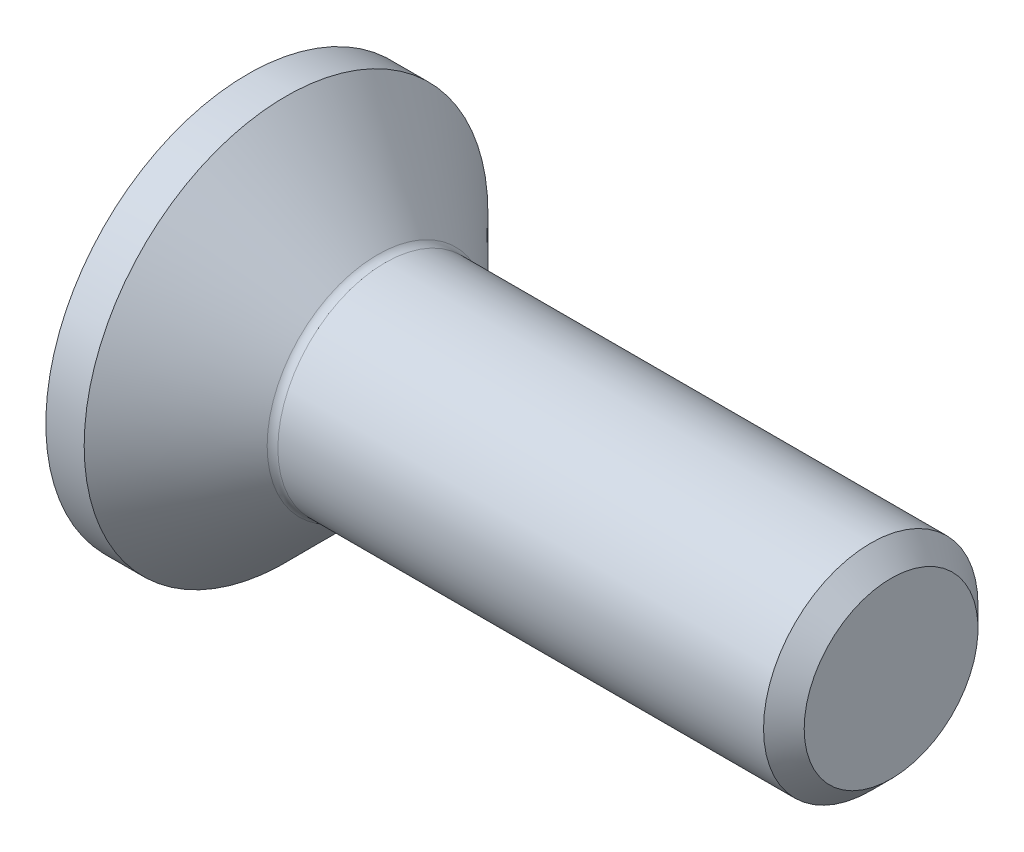
SolidWorks part; units mm, degrees
ref_plane "Front" through (0, 0, 0) normal (0, 0, 1) x (1, 0, 0)
ref_plane "Top" through (0, 0, 0) normal (0, 1, 0) x (1, 0, 0)
ref_plane "Right" through (0, 0, 0) normal (1, 0, 0) x (0, 0, -1)
sketch "Sketch1" plane through (0, 0, 0) normal (0, 0, 1) x (1, 0, 0)
  line L0 (0, 0) -> (0, 4.48)
  line L1 (0, 4.48) -> (2.48, 2)
  line L2 (2.48, 2) -> (12, 2)
  line L3 (12, 2) -> (12, 0)
  line L4 (12, 0) -> (0, 0)
  line L5 (-0.5871, 0) -> (5.4927, 0) construction
  dimension "l" = 12
  dimension "k" = 2.48
  dimension "d" = 4
  dimension "D1" = 45
revolve "Base" add sketch "Sketch1" angle 360 about L5
cosmetic thread "ThreadCosmetic1" parameters "b"=9.5, "D2"=3.242
sketch "Sketch2" plane through (0, 0, 0) normal (1, 0, 0) x (0, 0, -1)
  line L1 (1.4434, 0) -> (0.7217, 1.25)
  line L2 (0.7217, 1.25) -> (-0.7217, 1.25)
  line L3 (-0.7217, 1.25) -> (-1.4434, 0)
  line L4 (-1.4434, 0) -> (-0.7217, -1.25)
  line L5 (-0.7217, -1.25) -> (0.7217, -1.25)
  line L6 (0.7217, -1.25) -> (1.4434, 0)
  circle A0 centre (0, 0) radius 1.25 construction
  dimension "s" = 2.5
extrude "HexagonSocket" cut sketch "Sketch2" along normal blind 1.5
sketch "Sketch3" plane through (0, 0, 0) normal (0, 0, 1) x (1, 0, 0)
  line L0 (-0.4391, 0) -> (4.425, 0) construction
  line L1 (1.5, 0) -> (1.5, -1.25) construction
  line L2 (1.5, 1.25) -> (2.2217, 0)
  line L3 (2.2217, 0) -> (1.5, -1.25) construction
  line L4 (1.5, 1.25) -> (1.5, 0)
  line L5 (1.5, 0) -> (2.2217, 0)
  line L7 (1.5, 1.25) -> (1.5, 0) construction
  dimension "D1" = 120
revolve "Cut-Revolve1" cut sketch "Sketch3" angle 360 about L0
fillet "HeadFillet" radius 0.2 1 edges at (2.48, 0, 2)
chamfer "Chamfer" distance 0.379 angle 45 1 edges at (12, 0, 2)
sketch "Sketch4" plane through (0, 0, 0) normal (0, 1, 0) x (1, 0, 0)
  line L0 (11.8531, 0) -> (-2.694, 0) construction
  line L1 (-2, 8.765) -> (3, 8.765)
  line L2 (-2, 8.765) -> (-2, 3.765)
  line L3 (-2, 3.765) -> (3, 3.765)
  line L4 (3, 8.765) -> (3, 3.765)
  line L5 (0, 4.48) -> (0, -4.48) construction
  dimension "dk" = 7.53
  dimension "D2" = 2
  dimension "D3" = 5
  dimension "D4" = 5
revolve "Cut-Revolve2" cut sketch "Sketch4" angle 360 about L0
sketch "Sketch5" plane through (0, 0, 0) normal (0, 0, 1) x (1, 0, 0)
  line L0 (11.621, 1.6718) -> (11.8105, 2)
  line L1 (11.8105, 2) -> (11.8105, 2.379)
  line L2 (11.8105, 2.379) -> (11.4315, 2.379)
  line L3 (11.4315, 2.379) -> (11.4315, 2)
  line L4 (11.4315, 2) -> (11.621, 1.6718)
  line L5 (0, 0) -> (10.6885, 0) construction
  line L6 (11.621, 2) -> (11.621, -2) construction
  dimension "D1" = 4
  dimension "D2" = 0.379
revolve "Cut-Revolve10" [suppressed] cut sketch "Sketch5" angle 360 about L5
pattern_linear "LPattern10" [suppressed] count 21 spacing 0.4548 along (1, 0, 0)
equation "\"D1@Chamfer\" = (  \"d@Sketch1\" - \"D2@ThreadCosmetic1\" )  / 2"
equation "\"D1@Sketch5\" = \"d@Sketch1\""
equation "\"D2@Sketch5\" =  ( \"d@Sketch1\" - \"D2@ThreadCosmetic1\" )  / 2"
equation "\"D3@LPattern10\" = \"D2@Sketch5\" * 1.2"
equation "\"D1@LPattern10\" = \"b@ThreadCosmetic1\" / \"D3@LPattern10\""
